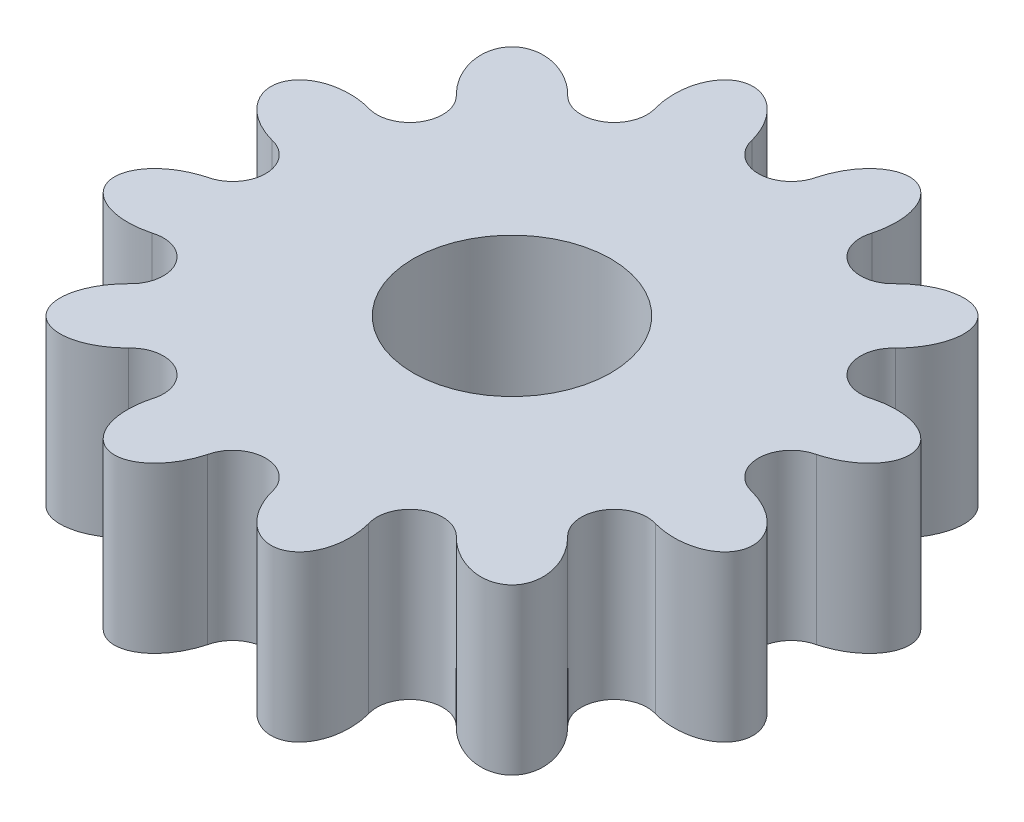
SolidWorks part; units mm, degrees
ref_plane "Front Plane" through (0, 0, 0) normal (0, 0, 1) x (1, 0, 0)
ref_plane "Top Plane" through (0, 0, 0) normal (0, 1, 0) x (1, 0, 0)
ref_plane "Right Plane" through (0, 0, 0) normal (1, 0, 0) x (0, 0, -1)
sketch "Sketch2" plane through (0, 0, 0) normal (0, 1, 0) x (1, 0, 0)
  line L0 (1.9525, 16.519) -> (2.685, 19.819)
  line L1 (0, 16.9523) -> (0, 0) construction
  line L2 (0, 0) -> (-2.3596, 19.8603) construction
  line L3 (-1.9525, 16.519) -> (-2.685, 19.819)
  line L4 (9.9504, 13.3296) -> (12.2347, 15.8212)
  line L5 (6.5686, 15.2821) -> (7.5842, 18.5062)
  line L6 (15.2821, 6.5686) -> (18.5062, 7.5842)
  line L7 (13.3296, 9.9504) -> (15.8212, 12.2347)
  line L8 (16.519, -1.9525) -> (19.819, -2.685)
  line L9 (16.519, 1.9525) -> (19.819, 2.685)
  line L10 (13.3296, -9.9504) -> (15.8212, -12.2347)
  line L11 (15.2821, -6.5686) -> (18.5062, -7.5842)
  line L12 (6.5686, -15.2821) -> (7.5842, -18.5062)
  line L13 (9.9504, -13.3296) -> (12.2347, -15.8212)
  line L14 (-1.9525, -16.519) -> (-2.685, -19.819)
  line L15 (1.9525, -16.519) -> (2.685, -19.819)
  line L16 (-9.9504, -13.3296) -> (-12.2347, -15.8212)
  line L17 (-6.5686, -15.2821) -> (-7.5842, -18.5062)
  line L18 (-15.2821, -6.5686) -> (-18.5062, -7.5842)
  line L19 (-13.3296, -9.9504) -> (-15.8212, -12.2347)
  line L20 (-16.519, 1.9525) -> (-19.819, 2.685)
  line L21 (-16.519, -1.9525) -> (-19.819, -2.685)
  line L22 (-13.3296, 9.9504) -> (-15.8212, 12.2347)
  line L23 (-15.2821, 6.5686) -> (-18.5062, 7.5842)
  line L24 (-6.5686, 15.2821) -> (-7.5842, 18.5062)
  line L25 (-9.9504, 13.3296) -> (-12.2347, 15.8212)
  arc A0 (-2.685, 19.819) -> (-7.5842, 18.5062) centre (0, 0) ccw
  arc A2 (-1.9525, 16.519) -> (1.9525, 16.519) centre (0, 16.9523) ccw
  arc A3 (6.5686, 15.2821) -> (9.9504, 13.3296) centre (8.4762, 14.6812) ccw
  arc A4 (13.3296, 9.9504) -> (15.2821, 6.5686) centre (14.6812, 8.4762) ccw
  arc A5 (16.519, 1.9525) -> (16.519, -1.9525) centre (16.9523, 0) ccw
  arc A6 (15.2821, -6.5686) -> (13.3296, -9.9504) centre (14.6812, -8.4762) ccw
  arc A7 (9.9504, -13.3296) -> (6.5686, -15.2821) centre (8.4762, -14.6812) ccw
  arc A8 (1.9525, -16.519) -> (-1.9525, -16.519) centre (0, -16.9523) ccw
  arc A9 (-6.5686, -15.2821) -> (-9.9504, -13.3296) centre (-8.4762, -14.6812) ccw
  arc A10 (-13.3296, -9.9504) -> (-15.2821, -6.5686) centre (-14.6812, -8.4762) ccw
  arc A11 (-16.519, -1.9525) -> (-16.519, 1.9525) centre (-16.9523, 0) ccw
  arc A12 (-15.2821, 6.5686) -> (-13.3296, 9.9504) centre (-14.6812, 8.4762) ccw
  arc A13 (-9.9504, 13.3296) -> (-6.5686, 15.2821) centre (-8.4762, 14.6812) ccw
  arc A14 (7.5842, 18.5062) -> (2.685, 19.819) centre (0, 0) ccw
  arc A15 (15.8212, 12.2347) -> (12.2347, 15.8212) centre (0, 0) ccw
  arc A16 (19.819, 2.685) -> (18.5062, 7.5842) centre (0, 0) ccw
  arc A17 (18.5062, -7.5842) -> (19.819, -2.685) centre (0, 0) ccw
  arc A18 (12.2347, -15.8212) -> (15.8212, -12.2347) centre (0, 0) ccw
  arc A19 (2.685, -19.819) -> (7.5842, -18.5062) centre (0, 0) ccw
  arc A20 (-7.5842, -18.5062) -> (-2.685, -19.819) centre (0, 0) ccw
  arc A21 (-15.8212, -12.2347) -> (-12.2347, -15.8212) centre (0, 0) ccw
  arc A22 (-19.819, -2.685) -> (-18.5062, -7.5842) centre (0, 0) ccw
  arc A23 (-18.5062, 7.5842) -> (-19.819, 2.685) centre (0, 0) ccw
  arc A24 (-12.2347, 15.8212) -> (-15.8212, 12.2347) centre (0, 0) ccw
  point P14 (2.685, 19.819)
  point P68 (0, 0)
  dimension "D1" = 20
  dimension "D5" = 12
  dimension "D4" = 2
  dimension "D2" = 3.3803
  dimension "D3" = 25.03
extrude "Boss-Extrude2" add sketch "Sketch2" along normal mid plane 10
sketch "Sketch4" plane through (0, 5, 0) normal (0, 1, 0) x (1, 0, 0)
  circle A0 centre (0, 0) radius 6
  dimension "D1" = 12
extrude "Cut-Extrude3" cut sketch "Sketch4" against normal blind 10
sketch "Sketch5" plane through (0, 5, 0) normal (0, 1, 0) x (1, 0, 0)
  line L0 (1.9525, 16.519) -> (6.5686, 15.2821) construction
  line L1 (0, 0) -> (8.1045, 16.8746) construction
  line L2 (0, 0) -> (5.1764, 19.3185) construction
  arc A0 (7.5842, 18.5062) -> (2.685, 19.819) centre (0, 0) ccw construction
  arc A1 (6.5686, 15.2821) -> (1.9525, 16.519) centre (4.93, 18.3992) ccw
  ellipse E0 centre (4.2605, 15.9005) end of major axis (3.3447, 12.4825) minor radius 2.3895 (6.5686, 15.2821) -> (1.9525, 16.519) ccw
  dimension "D1" = 3.5215
  dimension "D2" = 20
extrude "Cut-Extrude4" cut sketch "Sketch5" against normal blind 10
pattern_circular "CirPattern1" count 12 over 360 about axis through (0, 5, 0) along (0, 1, 0) of "Cut-Extrude4"
